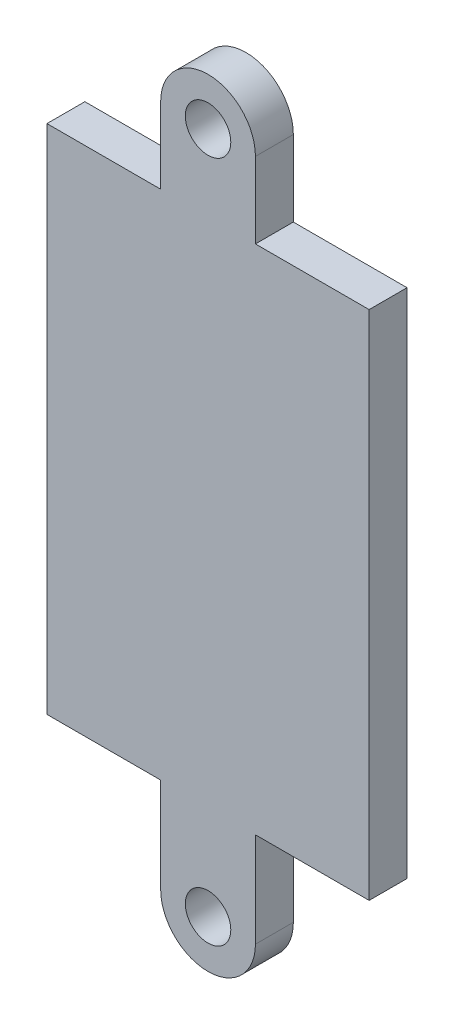
SolidWorks part; units mm, degrees
ref_plane "Front Plane" through (0, 0, 0) normal (0, 0, 1) x (1, 0, 0)
ref_plane "Top Plane" through (0, 0, 0) normal (0, 1, 0) x (1, 0, 0)
ref_plane "Right Plane" through (0, 0, 0) normal (1, 0, 0) x (0, 0, -1)
sketch "Sketch1" plane through (0, 0, 0) normal (0, 0, 1) x (1, 0, 0)
  line L0 (7.62, 39.37) -> (7.62, 34.29)
  line L1 (0, 0) -> (21.59, 0)
  line L2 (0, 0) -> (0, 34.29)
  line L3 (0, 34.29) -> (21.59, 34.29)
  line L4 (21.59, 0) -> (21.59, 34.29)
  line L5 (13.97, 39.37) -> (13.97, 34.29)
  line L6 (7.62, -6.35) -> (7.62, 0)
  line L7 (13.97, -6.35) -> (13.97, 0)
  circle A0 centre (10.795, -6.35) radius 3.175
  circle A1 centre (10.795, -6.35) radius 1.524
  circle A2 centre (10.795, 39.37) radius 3.175
  circle A3 centre (10.795, 39.37) radius 1.524
  dimension "D1" = 3.048
  dimension "D2" = 6.35
  dimension "D8" = 45.72
  dimension "D3" = 34.29
  dimension "D4" = 21.59
  dimension "D5" = 10.795
  dimension "D6" = 6.35
  dimension "D7" = 2
extrude "Boss-Extrude1" add sketch "Sketch1" along normal blind 2.54 contours A2 A3 | A2 L0 L3 L5 | L1 L4 L3 L2 | A0 L7 L1 L6 | A0 A1
